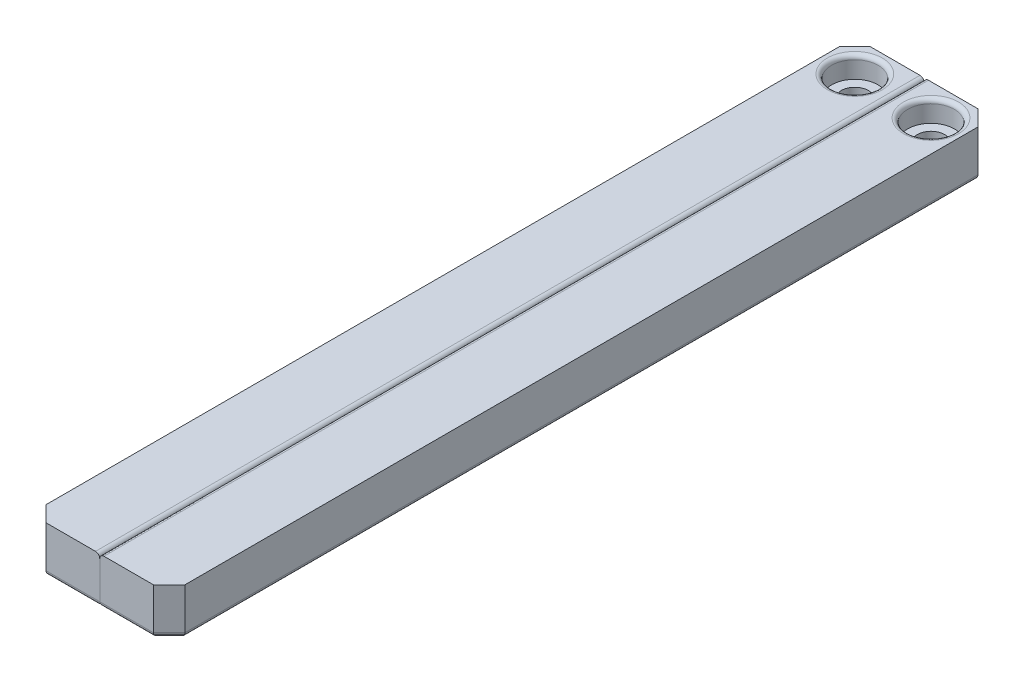
SolidWorks part; units mm, degrees
ref_plane "前视基准面" through (0, 0, 0) normal (0, 0, 1) x (1, 0, 0)
ref_plane "上视基准面" through (0, 0, 0) normal (0, 1, 0) x (1, 0, 0)
ref_plane "右视基准面" through (0, 0, 0) normal (1, 0, 0) x (0, 0, -1)
other "Configuration Table"
sketch "草图1" plane through (0, 0, 0) normal (0, 1, 0) x (1, 0, 0)
  line L0 (21.7593, 0) -> (29.9593, 0)
  line L1 (29.9593, 0) -> (29.9593, 97.4)
  line L2 (29.9593, 97.4) -> (21.7593, 97.4)
  line L3 (21.7593, 97.4) -> (21.7593, 0)
extrude "凸台-拉伸1" add sketch "草图1" along normal blind 5.4
sketch "草图2" plane through (0, 5.4, 0) normal (0, 1, 0) x (1, 0, 0)
  line L0 (21.7593, 97.4) -> (23.6093, 97.4)
  line L1 (29.9593, 97.4) -> (21.7593, 97.4) construction
  line L2 (21.7593, 97.4) -> (21.7593, 95.55)
  line L3 (21.7593, 97.4) -> (21.7593, 0) construction
  line L4 (21.7593, 95.55) -> (23.6093, 97.4)
  line L5 (21.7593, 0) -> (23.6093, 0)
  line L6 (21.7593, 0) -> (29.9593, 0) construction
  line L7 (21.7593, 0) -> (21.7593, 1.85)
  line L8 (21.7593, 1.85) -> (23.6093, 0)
  circle A0 centre (25.4593, 93.7) radius 1.6
extrude "切除-拉伸1" cut sketch "草图2" against normal through all
fillet "圆角1" radius 0.5 7 edges at (22.6843, 0, -0.925) (26.7843, 0, 0) (29.9593, 0, -48.7) (26.7843, 0, -97.4) (22.6843, 0, -96.475) (21.7593, 0, -48.7) (25.4593, 0, -92.1)
fillet "圆角2" radius 0.5 1 edges at (29.9593, 5.4, -48.7)
sketch "草图3" plane through (0, 5.4, 0) normal (0, 1, 0) x (1, 0, 0)
  circle A0 centre (25.4593, 93.7) radius 2.75
extrude "切除-拉伸2" cut sketch "草图3" against normal blind 2.5
fillet "圆角3" radius 0.5 1 edges at (25.4593, 5.4, -90.95)
mirror "镜向1" about plane through (29.9593, 5.4, 0) normal (-1, 0, 0) of bodies 108
